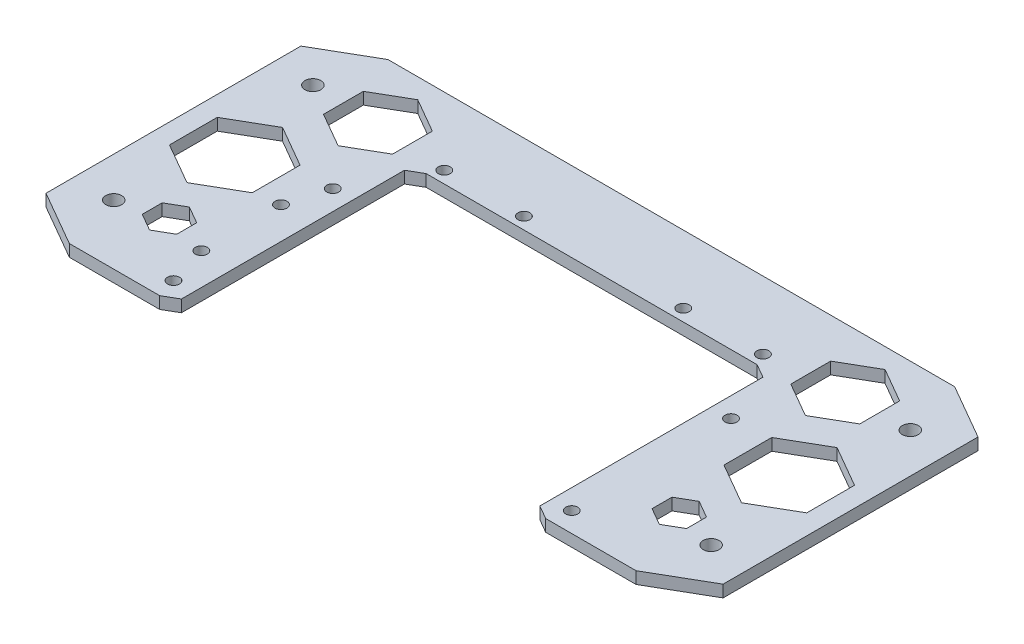
SolidWorks part; units mm, degrees
ref_plane "前视基准面" through (0, 0, 0) normal (0, 0, 1) x (1, 0, 0)
ref_plane "上视基准面" through (0, 0, 0) normal (0, 1, 0) x (1, 0, 0)
ref_plane "右视基准面" through (0, 0, 0) normal (1, 0, 0) x (0, 0, -1)
sketch "草图1" plane through (0, 0, 0) normal (0, 1, 0) x (1, 0, 0)
  line L0 (85, 80) -> (85, 0) construction
  line L1 (0, 0) -> (170, 0)
  line L2 (0, 0) -> (0, 80)
  line L3 (0, 80) -> (170, 80)
  line L4 (170, 0) -> (170, 80)
  line L5 (0, 40) -> (85, 40) construction
  circle A0 centre (10, 65) radius 2
  circle A1 centre (10, 15) radius 2
  circle A2 centre (160, 15) radius 2
  circle A3 centre (160, 65) radius 2
  dimension "D2" = 4
  dimension "D3" = 10
  dimension "D4" = 50
  dimension "D1" = 170
  dimension "D5" = 80
extrude "凸台-拉伸1" add sketch "草图1" along normal blind 3
sketch "草图2" plane through (0, 3, 0) normal (0, 1, 0) x (1, 0, 0)
  line L0 (85, 0) -> (85, 80) construction
  line L1 (0, 0) -> (170, 0) construction
  line L2 (170, 80) -> (0, 80) construction
  line L3 (35, 45) -> (35, 5) construction
  line L4 (40, 0) -> (130, 0)
  line L5 (40, 0) -> (40, 60)
  line L6 (40, 60) -> (130, 60)
  line L7 (130, 0) -> (130, 60)
  line L8 (45, 63) -> (65, 63) construction
  circle A0 centre (35, 45) radius 1.5
  circle A1 centre (35, 5) radius 1.5
  circle A2 centre (135, 5) radius 1.5
  circle A3 centre (135, 45) radius 1.5
  circle A4 centre (45, 63) radius 1.5
  circle A5 centre (65, 63) radius 1.5
  circle A6 centre (105, 63) radius 1.5
  circle A7 centre (125, 63) radius 1.5
  point P10 (85, 60)
  dimension "D3" = 3
  dimension "D4" = 5
  dimension "D6" = 3
  dimension "D9" = 40
  dimension "D10" = 3
  dimension "D11" = 100
  dimension "D1" = 60
  dimension "D2" = 90
  dimension "D5" = 40
  dimension "D8" = 20
  dimension "D7" = 2
extrude "切除-拉伸1" cut sketch "草图2" against normal through all
sketch "草图3" plane through (0, 3, 0) normal (0, 1, 0) x (1, 0, 0)
  line L0 (32, 35) -> (32, 15) construction
  line L1 (35, 5) -> (35, 45) construction
  line L2 (35, 25) -> (32, 25) construction
  circle A0 centre (32, 15) radius 1.5
  circle A1 centre (32, 35) radius 1.5
  dimension "D2" = 3
  dimension "D1" = 3
  dimension "D3" = 20
extrude "切除-拉伸2" cut sketch "草图3" against normal blind 5
sketch "草图5" plane through (0, 3, 0) normal (0, 1, 0) x (1, 0, 0)
  line L0 (85, 80) -> (85, 60) construction
  line L1 (15.3916, 28.0008) -> (25.7833, 34.0004)
  line L2 (25.7833, 34.0004) -> (25.7833, 45.9996)
  line L3 (25.7833, 45.9996) -> (15.3916, 51.9992)
  line L4 (15.3916, 51.9992) -> (5, 45.9996)
  line L5 (5, 45.9996) -> (5, 34.0004)
  line L6 (5, 34.0004) -> (15.3916, 28.0008)
  line L7 (35, 60) -> (35, 70)
  line L8 (35, 70) -> (26.3397, 75)
  line L9 (26.3397, 75) -> (17.6795, 70)
  line L10 (17.6795, 70) -> (17.6795, 60)
  line L11 (17.6795, 60) -> (26.3397, 55)
  line L12 (26.3397, 55) -> (35, 60)
  line L13 (21, 13) -> (25.3301, 15.5)
  line L14 (25.3301, 15.5) -> (25.3301, 20.5)
  line L15 (25.3301, 20.5) -> (21, 23)
  line L16 (21, 23) -> (16.6699, 20.5)
  line L17 (16.6699, 20.5) -> (16.6699, 15.5)
  line L18 (16.6699, 15.5) -> (21, 13)
  line L19 (170, 80) -> (0, 80) construction
  line L20 (130, 60) -> (40, 60) construction
  line L21 (40, 60) -> (40, 0) construction
  line L22 (15.3916, 40) -> (0, 40) construction
  line L23 (0, 80) -> (0, 0) construction
  line L24 (21, 18) -> (21, 0) construction
  line L26 (0, 0) -> (40, 0) construction
  line L27 (149, 18) -> (149, 0) construction
  line L34 (154.6084, 40) -> (170, 40) construction
  line L35 (153.3301, 15.5) -> (149, 13)
  line L36 (153.3301, 20.5) -> (153.3301, 15.5)
  line L37 (149, 23) -> (153.3301, 20.5)
  line L38 (144.6699, 20.5) -> (149, 23)
  line L39 (144.6699, 15.5) -> (144.6699, 20.5)
  line L40 (149, 13) -> (144.6699, 15.5)
  line L41 (143.6603, 55) -> (135, 60)
  line L42 (152.3205, 60) -> (143.6603, 55)
  line L43 (152.3205, 70) -> (152.3205, 60)
  line L44 (143.6603, 75) -> (152.3205, 70)
  line L45 (135, 70) -> (143.6603, 75)
  line L46 (135, 60) -> (135, 70)
  line L47 (165, 34.0004) -> (154.6084, 28.0008)
  line L48 (165, 45.9996) -> (165, 34.0004)
  line L49 (154.6084, 51.9992) -> (165, 45.9996)
  line L50 (144.2167, 45.9996) -> (154.6084, 51.9992)
  line L51 (144.2167, 34.0004) -> (144.2167, 45.9996)
  line L52 (154.6084, 28.0008) -> (144.2167, 34.0004)
  circle A0 centre (15.3916, 40) radius 10.3916 construction
  circle A1 centre (26.3397, 65) radius 8.6603 construction
  circle A2 centre (21, 18) radius 4.3301 construction
  circle A3 centre (149, 18) radius 4.3301 construction
  circle A4 centre (143.6603, 65) radius 8.6603 construction
  circle A5 centre (154.6084, 40) radius 10.3916 construction
  dimension "D1" = 5
  dimension "D2" = 10
  dimension "D3" = 15
  dimension "D4" = 5
  dimension "D5" = 5
  dimension "D6" = 11.9992
  dimension "D7" = 19
  dimension "D8" = 18
extrude "切除-拉伸3" cut sketch "草图5" against normal blind 10
chamfer "倒角1" distance 2 angle 60 4 edges at (130, 1.5, 0) (130, 1.5, -60) (40, 1.5, -60) (40, 1.5, 0)
chamfer "倒角2" distance 8 angle 60 4 edges at (170, 1.5, -80) (170, 1.5, 0) (0, 1.5, 0) (0, 1.5, -80)
